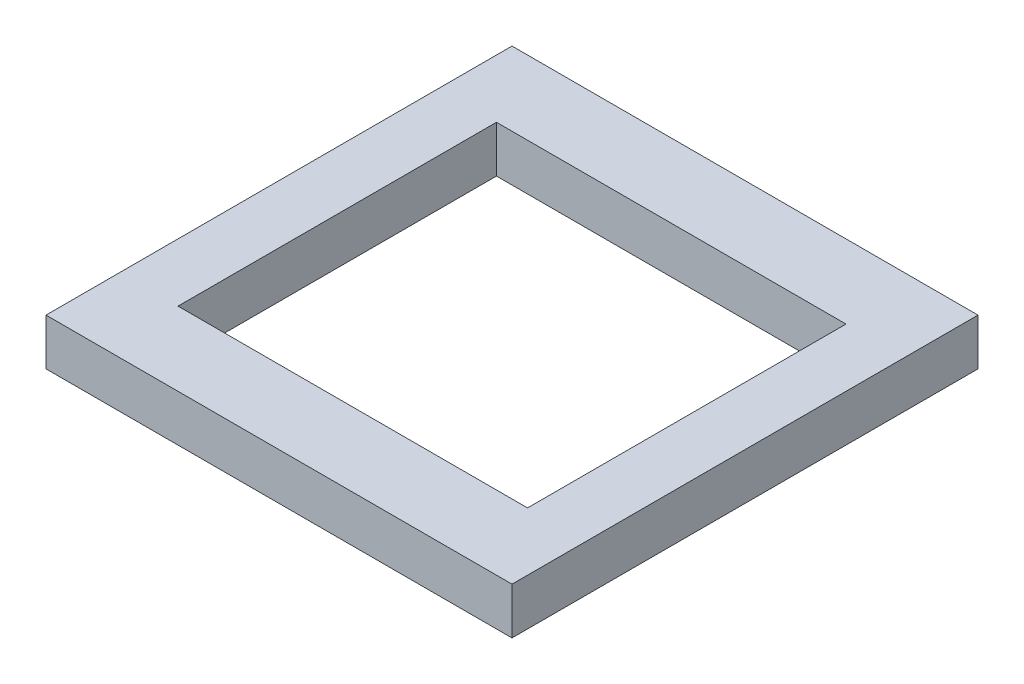
SolidWorks part; units mm, degrees
ref_plane "Front Plane" through (0, 0, 0) normal (0, 0, 1) x (1, 0, 0)
ref_plane "Top Plane" through (0, 0, 0) normal (0, 1, 0) x (1, 0, 0)
ref_plane "Right Plane" through (0, 0, 0) normal (1, 0, 0) x (0, 0, -1)
sketch "Sketch1" plane through (0, 0, 0) normal (0, 1, 0) x (1, 0, 0)
  line L1 (-30, 30) -> (30, 30)
  line L2 (-30, 30) -> (-30, -30)
  line L3 (-30, -30) -> (30, -30)
  line L4 (30, 30) -> (30, -30)
  line L5 (-30, 30) -> (30, -30) construction
  line L6 (-30, -30) -> (30, 30) construction
  line L7 (-22.5, 20.5) -> (22.5, 20.5)
  line L8 (-22.5, 20.5) -> (-22.5, -20.5)
  line L9 (-22.5, -20.5) -> (22.5, -20.5)
  line L10 (22.5, 20.5) -> (22.5, -20.5)
  line L11 (-22.5, 20.5) -> (22.5, -20.5) construction
  line L12 (-22.5, -20.5) -> (22.5, 20.5) construction
  point P0 (0, 0)
  point P6 (0, 0)
  dimension "D1" = 60
  dimension "D2" = 60
  dimension "D3" = 45
  dimension "D4" = 41
extrude "Boss-Extrude1" add sketch "Sketch1" along normal blind 6
